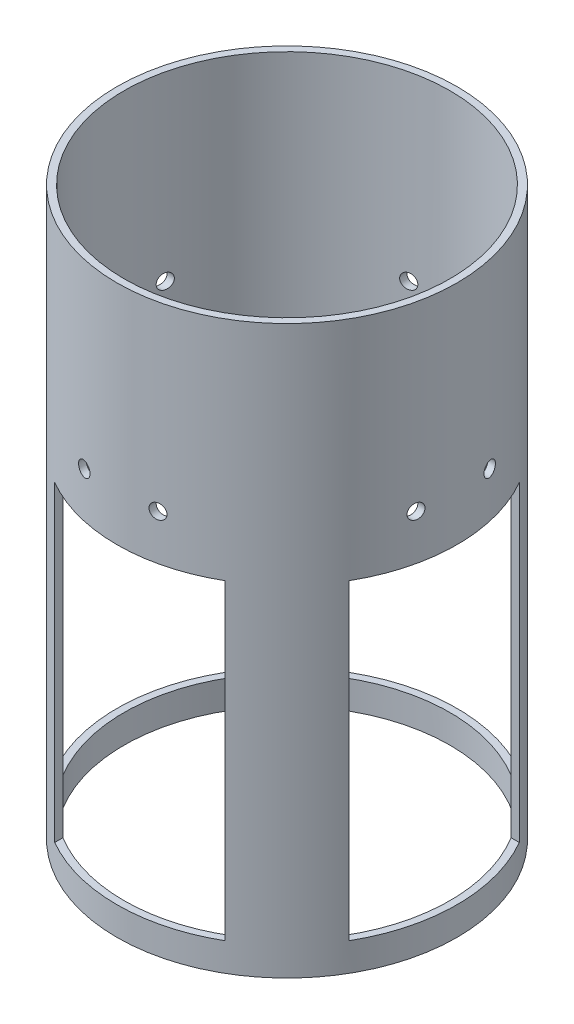
SolidWorks part; units mm, degrees
ref_plane "Front Plane" through (0, 0, 0) normal (0, 0, 1) x (1, 0, 0)
ref_plane "Top Plane" through (0, 0, 0) normal (0, 1, 0) x (1, 0, 0)
ref_plane "Right Plane" through (0, 0, 0) normal (1, 0, 0) x (0, 0, -1)
sketch "Sketch1" plane through (0, 0, 0) normal (0, 1, 0) x (1, 0, 0)
  circle A0 centre (0, 0) radius 76.2
  circle A1 centre (0, 0) radius 73.025
extrude "Boss-Extrude1" add sketch "Sketch1" along normal blind 254
sketch "Sketch5" plane through (0, 0, 0) normal (0, -1, 0) x (1, 0, 0)
  line L0 (0, 76.2) -> (0, -76.2) construction
  circle A0 centre (0, 0) radius 76.2 construction
ref_plane "Plane2" through (0, 0, -76.2) normal (0, 0, -1) x (-1, 0, 0)
sketch "Sketch6" plane through (0, 0, -76.2) normal (0, 0, -1) x (-1, 0, 0)
  line L0 (0, 254) -> (0, 152.4) construction
  line L1 (73.025, 254) -> (-73.025, 254) construction
  line L2 (0, 152.4) -> (-38.1, 152.4) construction
  line L7 (0, 152.4) -> (38.1, 152.4) construction
  line L8 (-38.1, 152.4) -> (38.1, 152.4)
  line L9 (-38.1, 152.4) -> (-38.1, 12.7)
  line L10 (38.1, 152.4) -> (38.1, 12.7)
  line L11 (-38.1, 12.7) -> (38.1, 12.7)
extrude "Cut-Extrude6" cut sketch "Sketch6" against normal blind 20.574
pattern_circular "CirPattern9" count 4 over 360 about axis through (0, 0, 0) along (0, 1, 0) of "Cut-Extrude6"
sketch "Sketch7" plane through (0, 0, -76.2) normal (0, 0, -1) x (-1, 0, 0)
  line L0 (0, 0) -> (0, 152.4) construction
  line L1 (0, 152.4) -> (0, 172.72) construction
  line L2 (16.51, 172.72) -> (-16.51, 172.72) construction
  circle A0 centre (-16.51, 172.72) radius 3.302
  circle A1 centre (16.51, 172.72) radius 3.302
  point P6 (0, 172.72)
extrude "Cut-Extrude7" cut sketch "Sketch7" against normal blind 17.78
pattern_circular "CirPattern10" count 4 over 360 about axis through (0, 254, 0) along (0, 1, 0) of "Cut-Extrude7"
